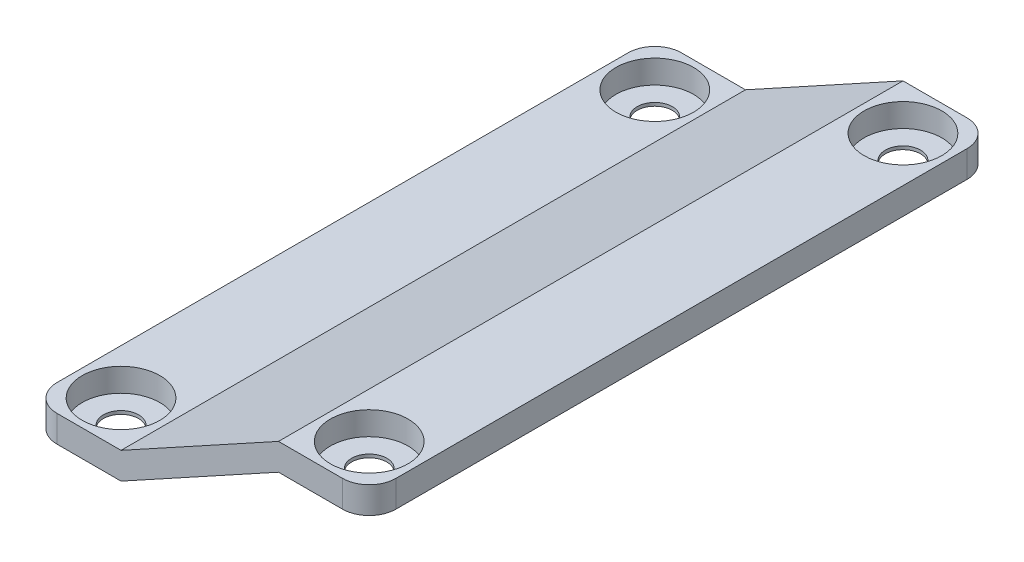
SolidWorks part; units mm, degrees
ref_plane "Front Plane" through (0, 0, 0) normal (0, 0, 1) x (1, 0, 0)
ref_plane "Top Plane" through (0, 0, 0) normal (0, 1, 0) x (1, 0, 0)
ref_plane "Right Plane" through (0, 0, 0) normal (1, 0, 0) x (0, 0, -1)
sketch "Sketch1" plane through (0, 0, 0) normal (0, 0, 1) x (1, 0, 0)
  line L0 (-15.0078, -4.569) -> (14.4922, 11.631)
  line L1 (-15.0078, -9.569) -> (-32.0078, -9.569)
  line L2 (-15.0078, -4.569) -> (-32.0078, -4.569)
  line L3 (-32.0078, -9.569) -> (-32.0078, -4.569)
  line L4 (14.4922, 6.631) -> (31.4922, 6.631)
  line L5 (14.4922, 11.631) -> (31.4922, 11.631)
  line L6 (31.4922, 6.631) -> (31.4922, 11.631)
  line L7 (-15.0078, -9.569) -> (14.4922, 6.631)
extrude "Cover Body" add sketch "Sketch1" against normal blind 117
sketch "Screw Hole outlines" plane through (0, -4.569, 0) normal (0, 1, 0) x (1, 0, 0)
  line L0 (14.4922, 117) -> (-15.0078, 117) construction
  line L1 (-23.5078, 108.5) -> (22.9922, 108.5) construction
  line L2 (-23.5078, 108.5) -> (-23.5078, 8.5) construction
  line L3 (-23.5078, 8.5) -> (22.9922, 8.5) construction
  line L4 (22.9922, 108.5) -> (22.9922, 8.5) construction
  line L6 (31.4922, 117) -> (31.4922, 0) construction
  dimension "D1" = 8.5
  dimension "D2" = 8.5
hole_wizard "CBORE for M6 Hex Head Bolt1" positions "Sketch2" profile "Sketch4" counterbore size "M6" standard "ANSI Metric" end condition through all
sketch "Sketch2" plane through (0, -4.569, 0) normal (0, 1, 0) x (1, 0, 0)
  point P0 (-23.5078, 108.5)
  point P3 (-23.5078, 8.5)
sketch "Sketch4" plane through (-23.5078, -4.569, -108.5) normal (1, 0, 0) x (0, 0, 1)
  line L0 (0, 0) -> (0, 5)
  line L1 (0, 5) -> (3.3, 5)
  line L3 (3.3, 5) -> (3.3, 4.38)
  line L4 (3.3, 4.38) -> (7.275, 4.38)
  line L5 (7.275, 4.38) -> (7.275, 0)
  line L7 (7.275, 0) -> (0, 0)
  line L11 (0, -6.35) -> (0, 107.95) construction
  dimension "Thru Hole Dia." = 6.6
  dimension "Thru Hole Depth" = 5
  dimension "C'Bore Dia." = 14.55
  dimension "C'Bore Depth" = 4.38
ref_plane "Upper Lid Plane" through (22.9922, 0, 0) normal (1, 0, 0) x (0, 0, -1)
sketch "Sketch9" plane through (22.9922, 0, 0) normal (1, 0, 0) x (0, 0, -1)
  line L0 (8.5, -4.569) -> (8.5, 11.631) construction
  line L1 (108.5, -4.569) -> (8.5, -4.569) construction
  line L2 (108.5, -4.569) -> (8.5, -4.569) construction
  line L3 (117, 11.631) -> (0, 11.631) construction
  line L4 (85.5, -4.569) -> (85.5, 11.631) construction
  dimension "D1" = 77
hole_wizard "CBORE for M6 Hex Head Bolt2" positions "Sketch10" profile "Sketch11" counterbore size "M6" standard "ANSI Metric" end condition up to next
sketch "Sketch10" plane through (0, 11.631, 0) normal (0, 1, 0) x (1, 0, 0)
  line L0 (-23.5078, 108.5) -> (39.7843, 108.5) construction
  line L2 (22.9922, 115.1486) -> (22.9922, -7.1503) construction
  point P0 (22.9922, 8.5)
  point P19 (22.9922, 108.5)
  point P20 (0, 0)
  dimension "D1" = 100
sketch "Sketch11" plane through (22.9922, 11.631, -8.5) normal (1, 0, 0) x (0, 0, 1)
  line L0 (0, 0) -> (0, 5)
  line L1 (0, 5) -> (3.3, 5)
  line L3 (3.3, 5) -> (3.3, 4.38)
  line L4 (3.3, 4.38) -> (7.275, 4.38)
  line L5 (7.275, 4.38) -> (7.275, 0)
  line L7 (7.275, 0) -> (0, 0)
  line L11 (0, -6.35) -> (0, 107.95) construction
  dimension "Thru Hole Dia." = 6.6
  dimension "Thru Hole Depth" = 5
  dimension "C'Bore Dia." = 14.55
  dimension "C'Bore Depth" = 4.38
fillet "Fillet1" radius 5 4 edges at (-32.0078, -7.069, -117) (31.4922, 9.131, -117) (31.4922, 9.131, 0) (-32.0078, -7.069, 0)
